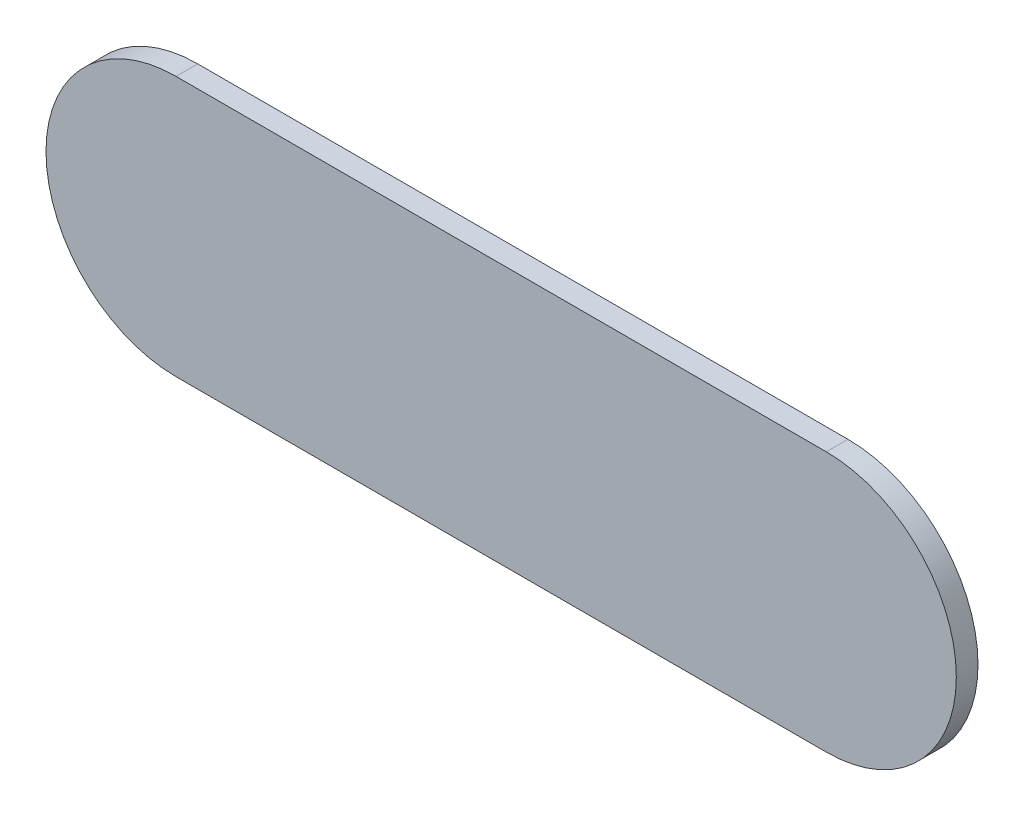
SolidWorks part; units mm, degrees
material "NEOPRENE"
ref_plane "Front" through (0, 0, 0) normal (0, 0, 1) x (1, 0, 0)
ref_plane "Top" through (0, 0, 0) normal (0, 1, 0) x (1, 0, 0)
ref_plane "Right" through (0, 0, 0) normal (1, 0, 0) x (0, 0, -1)
sketch "Sketch1" plane through (0, 0, 0) normal (0, 0, 1) x (1, 0, 0)
  line L0 (-15, 6) -> (15, 6)
  line L1 (-15, -6) -> (15, -6)
  line L2 (0, 6) -> (0, -6) construction
  arc A0 (-15, 6) -> (-15, -6) centre (-15, 0) ccw
  arc A1 (15, -6) -> (15, 6) centre (15, 0) ccw
  point P10 (0, 0)
  dimension "D1" = 12
  dimension "D2" = 30
extrude "Boss-Extrude1" add sketch "Sketch1" along normal blind 1
